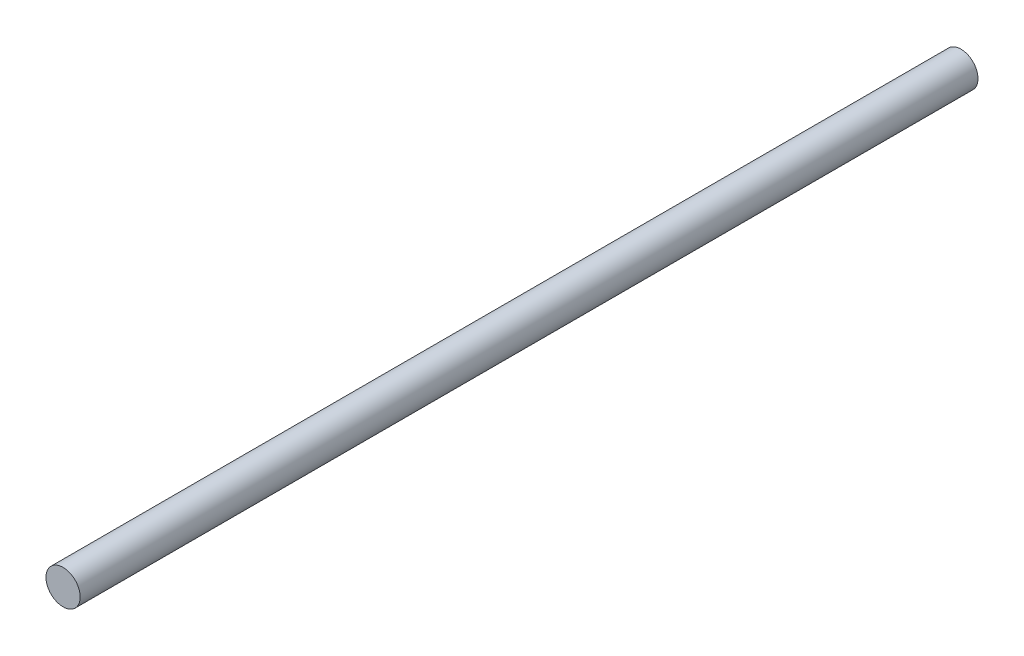
SolidWorks part; units mm, degrees
ref_plane "Front Plane" through (0, 0, 0) normal (0, 0, 1) x (1, 0, 0)
ref_plane "Top Plane" through (0, 0, 0) normal (0, 1, 0) x (1, 0, 0)
ref_plane "Right Plane" through (0, 0, 0) normal (1, 0, 0) x (0, 0, -1)
sketch "Sketch1" plane through (0, 0, 0) normal (0, 0, 1) x (1, 0, 0)
  circle A0 centre (0, 0) radius 8.89
  dimension "D1" = 17.78
extrude "Boss-Extrude1" add sketch "Sketch1" along normal blind 363.2 and the other way blind 103.2
